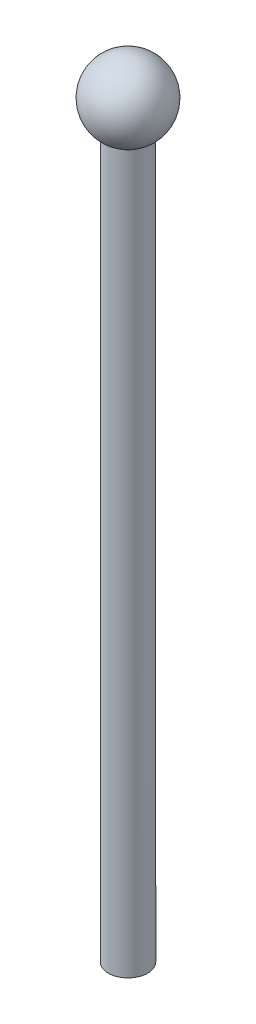
SolidWorks part; units mm, degrees
ref_plane "Front Plane" through (0, 0, 0) normal (0, 0, 1) x (1, 0, 0)
ref_plane "Top Plane" through (0, 0, 0) normal (0, 1, 0) x (1, 0, 0)
ref_plane "Right Plane" through (0, 0, 0) normal (1, 0, 0) x (0, 0, -1)
sketch "Sketch1" plane through (0, 0, 0) normal (0, 0, 1) x (1, 0, 0)
  line L0 (0, 3.75) -> (0, -76.25)
  line L1 (0, -76.25) -> (-2, -76.25)
  line L2 (-2, -76.25) -> (-2, -3.1721)
  circle A0 centre (0, 0) radius 3.75
  dimension "D1" = 7.5
  dimension "D2" = 2
  dimension "D3" = 80
revolve "Revolve1" add sketch "Sketch1" angle 360 about L0
